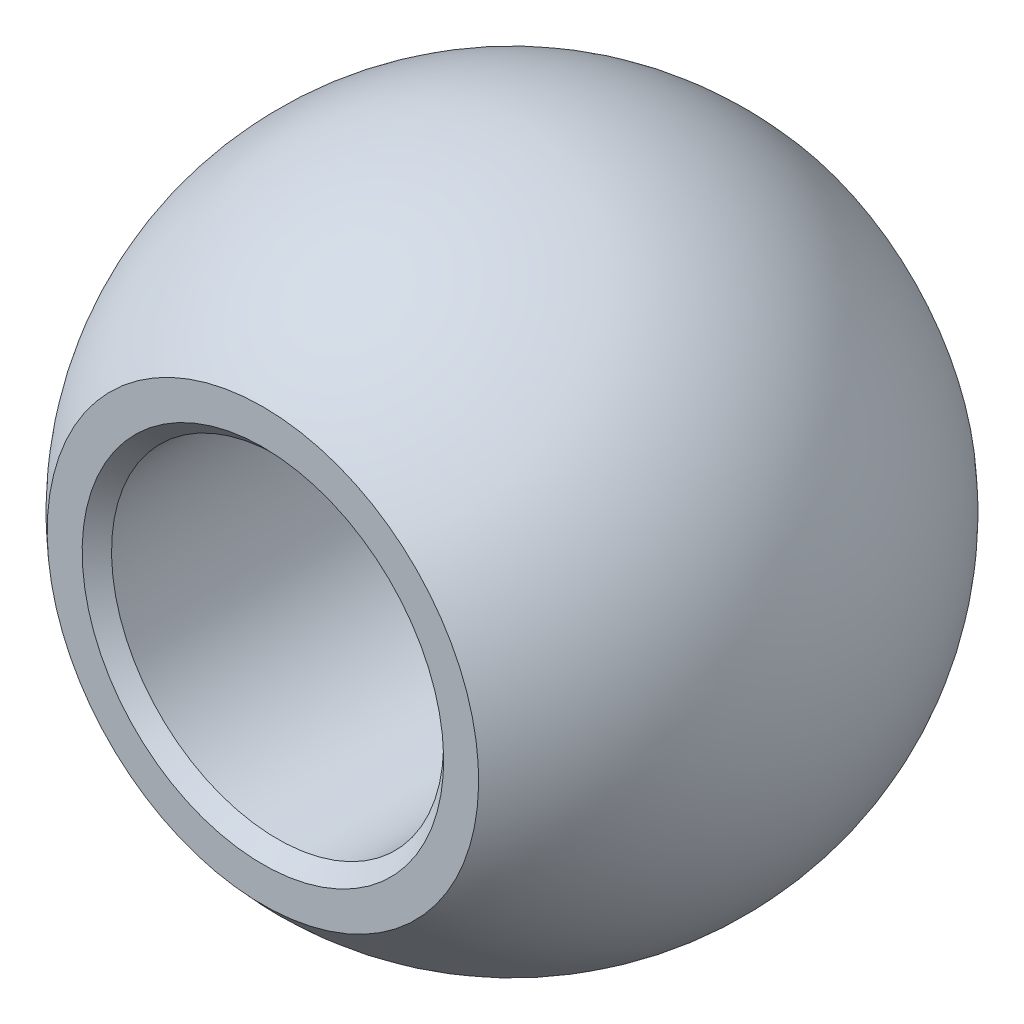
SolidWorks part; units mm, degrees
material "Chrome Stainless Steel"
ref_plane "Front" through (0, 0, 0) normal (0, 0, 1) x (1, 0, 0)
ref_plane "Top" through (0, 0, 0) normal (0, 1, 0) x (1, 0, 0)
ref_plane "Right" through (0, 0, 0) normal (1, 0, 0) x (0, 0, -1)
sketch "Sketch6" plane through (0, 0, 0) normal (0, 0, 1) x (1, 0, 0)
  line L0 (5.6464, 4) -> (-5.6464, 4)
  line L2 (0, 0) -> (-7.9375, 0) construction
  line L3 (6.8559, -4) -> (-6.8559, -4) construction
  line L4 (0, -4) -> (0, 4) construction
  line L5 (6, 4.3536) -> (6, 5.1965)
  line L6 (-6, 4.3536) -> (-6, 5.1965)
  line L7 (6, 4.3536) -> (5.6464, 4)
  line L8 (-6, 4.3536) -> (-5.6464, 4)
  line L9 (-6, 5.1965) -> (-7.9375, 0) construction
  line L10 (6, 7.1414) -> (6, 4.3536) construction
  line L11 (-6.9688, 2.5983) -> (-7.4374, 2.773) construction
  arc A0 (6, 5.1965) -> (-6, 5.1965) centre (0, 0) ccw
  arc A1 (-6, 5.1965) -> (6, 5.1965) centre (0, 0) ccw construction
  dimension "A" = 15.875
  dimension "D2" = 8
  dimension "B" = 12
  dimension "Chamfer-Angle" = 45
revolve "Ball" add sketch "Sketch6" angle 360 about L2
move or copy body "Body-Move/Copy1" bodies to move or copy 101 copy no rotation origin (0, 0, 0) rotation axis (0, 1, 0) rotation angle 90
